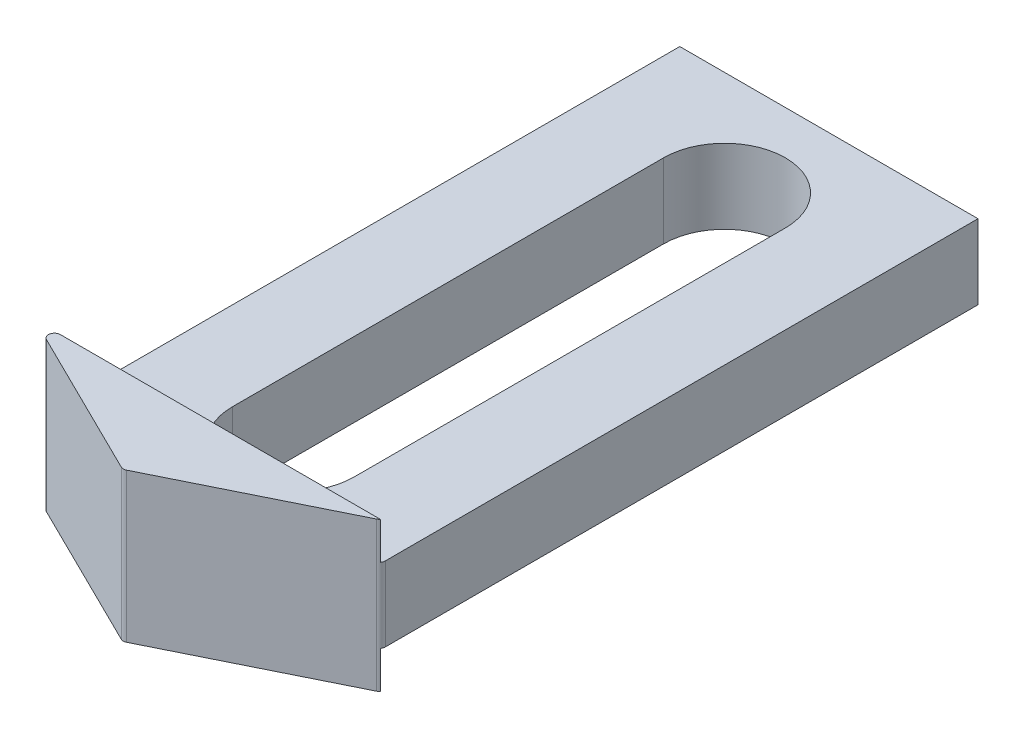
SolidWorks part; units mm, degrees
ref_plane "Front Plane" through (0, 0, 0) normal (0, 0, 1) x (1, 0, 0)
ref_plane "Top Plane" through (0, 0, 0) normal (0, 1, 0) x (1, 0, 0)
ref_plane "Right Plane" through (0, 0, 0) normal (1, 0, 0) x (0, 0, -1)
sketch "Sketch1" plane through (0, 0, 0) normal (0, 1, 0) x (1, 0, 0)
  line L0 (15.1691, 0) -> (7.7862, -3.6457)
  line L4 (15.1691, 0) -> (15.1691, 25.4)
  line L5 (2.4691, 25.4) -> (15.1691, 25.4)
  line L6 (0.4034, 0) -> (15.1691, 0) construction
  line L9 (0.4034, 0) -> (2.4691, 0)
  line L10 (2.4691, 25.4) -> (2.4691, 0)
  line L11 (7.7862, -3.6457) -> (0.4034, 0)
  point P0 (0, 0)
  point P2 (0, 0)
  point P3 (7.7862, 0)
  point P9 (15.1691, 0)
  point P10 (0, 0)
  point P12 (5.0627, -5.206)
  point P13 (1.4227, 0)
  point P14 (2.4691, 0)
  dimension "D1" = 25.4
  dimension "D2" = 12.7
extrude "Boss-Extrude1" add sketch "Sketch1" along normal mid plane 6.35
sketch "Sketch2" [suppressed] plane through (10.4887, 0, 0) normal (-1, 0, 0) x (0, 0, 1)
  line L0 (-12.7, 6.35) -> (-12.7, 0) construction
  line L1 (6.35, 6.35) -> (6.35, 0) construction
  point P0 (-8.89, 3.175)
  point P1 (2.54, 3.175)
  point P6 (-12.7, 3.175)
  dimension "D1" = 3.81
  dimension "D2" = 3.81
hole_wizard "#6 Clearance Hole1" [suppressed] positions "Sketch3" profile "Sketch4" hole size "#6" standard "ANSI Inch"
sketch "Sketch3" [suppressed] plane through (10.4887, 0, 0) normal (-1, 0, 0) x (0, 0, 1)
  point P0 (-8.89, 3.175)
  point P3 (2.54, 3.175)
sketch "Sketch4" plane through (10.4887, 3.175, -8.89) normal (0, 1, 0) x (0, 0, 1)
  line L0 (0, 0) -> (0, 7.874)
  line L1 (0, 7.874) -> (1.8986, 6.7332)
  line L2 (1.8986, 6.7332) -> (1.8986, 0)
  line L5 (1.8986, 0) -> (0, 0)
  line L10 (0, 7.874) -> (-1.8987, 6.7332) construction
  line L11 (0, -6.35) -> (0, 107.95) construction
  dimension "Hole Dia." = 3.7973
  dimension "Hole Depth" = 7.874
  dimension "Drill Angle" = 118
fillet "Fillet1" radius 0.254 4 edges at (2.4691, 0, 0) (15.1691, 0, 0) (0.4034, 0, 0) (7.7862, 0, 3.6457)
sketch "Sketch5" plane through (0, 3.175, 0) normal (0, 1, 0) x (1, 0, 0)
  line L0 (8.8191, 20.955) -> (8.8191, 2.5908) construction
  line L1 (11.4099, 20.955) -> (11.4099, 2.5908)
  line L2 (6.2283, 20.955) -> (6.2283, 2.5908)
  line L5 (2.4691, 25.4) -> (15.1691, 25.4) construction
  line L6 (1.4914, 0) -> (2.2151, 0) construction
  arc A0 (11.4099, 20.955) -> (6.2283, 20.955) centre (8.8191, 20.955) ccw
  arc A1 (6.2283, 2.5908) -> (11.4099, 2.5908) centre (8.8191, 2.5908) ccw
  point P2 (8.8191, 11.7729)
  point P7 (8.8191, 0)
  point P10 (13.6637, 8.8719)
  point P11 (13.6637, -2.8432)
  point P12 (7.6454, 2.0885)
  point P14 (0, 0)
  point P15 (13.6637, 3.4623)
  point P17 (8.8191, 25.4)
  dimension "D1" = 5.1816
  dimension "D2" = 4.445
extrude "Cut-Extrude1" cut sketch "Sketch5" against normal up to next
sketch "Sketch6" plane through (2.4691, 0, 0) normal (-1, 0, 0) x (0, 0, 1)
  line L1 (-25.4, 3.175) -> (0, 3.175)
  line L2 (-25.4, 3.175) -> (-25.4, 1.5875)
  line L3 (-25.4, 1.5875) -> (0, 1.5875)
  line L4 (0, 3.175) -> (0, 1.5875)
  line L11 (0, 3.175) -> (0, -3.175) construction
  line L13 (8.1212, 0) -> (-8.1212, 0) construction
  line L14 (-25.4, -3.175) -> (0, -3.175)
  line L15 (-25.4, -3.175) -> (-25.4, -1.5875)
  line L16 (-25.4, -1.5875) -> (0, -1.5875)
  line L17 (0, -3.175) -> (0, -1.5875)
  dimension "D1" = 3.175
  dimension "D2" = 1.5875
extrude "Cut-Extrude2" cut sketch "Sketch6" against normal through all both and the other way through all
